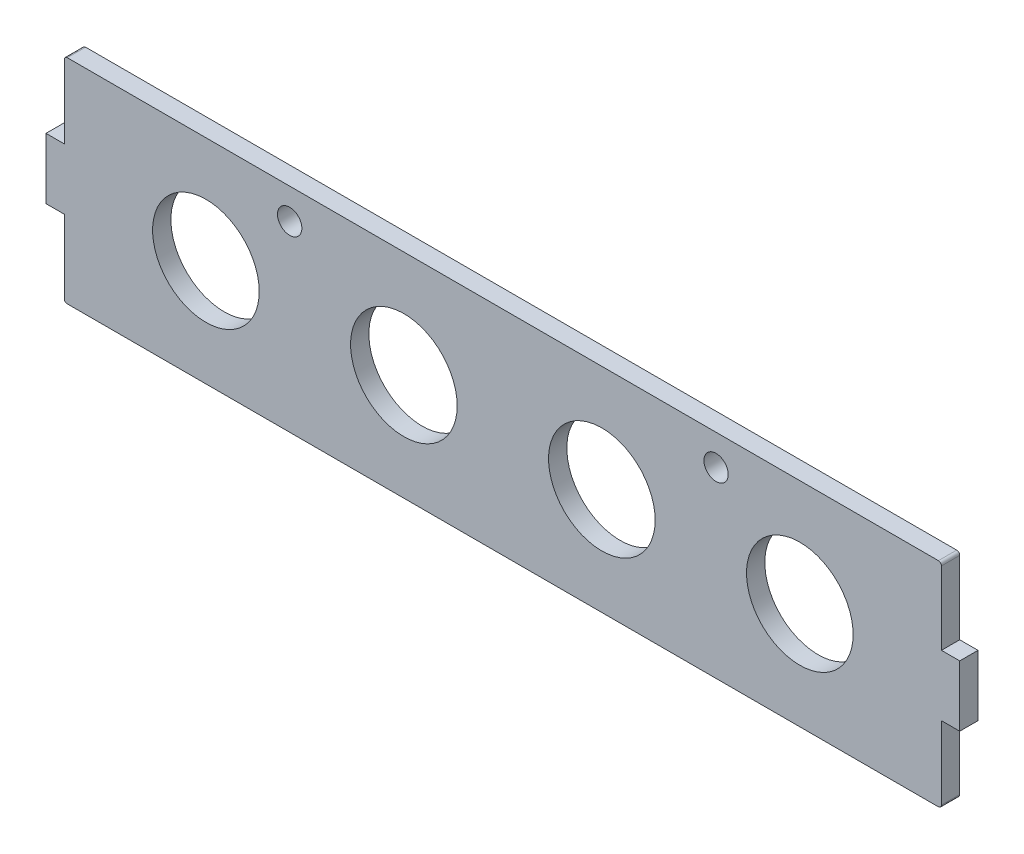
SolidWorks part; units mm, degrees
material "Beech"
ref_plane "Спереди" through (0, 0, 0) normal (0, 0, 1) x (1, 0, 0)
ref_plane "Сверху" through (0, 0, 0) normal (0, 1, 0) x (1, 0, 0)
ref_plane "Справа" through (0, 0, 0) normal (1, 0, 0) x (0, 0, -1)
sketch "Sketch1" plane through (0, 0, 0) normal (0, 0, 1) x (1, 0, 0)
  line L1 (0, 0) -> (300, 0)
  line L2 (0, 0) -> (0, 70)
  line L3 (0, 70) -> (300, 70)
  line L4 (300, 0) -> (300, 70)
  dimension "D1" = 70
  dimension "D2" = 300
extrude "front" add sketch "Sketch1" against normal blind 6
sketch "Sketch2" plane through (0, 0, 0) normal (0, 0, 1) x (1, 0, 0)
  line L0 (6, 70) -> (6, 45)
  line L1 (300, 70) -> (0, 70) construction
  line L2 (6, 45) -> (0, 45)
  line L3 (0, 70) -> (0, 0) construction
  line L4 (0, 25) -> (6, 25)
  line L5 (6, 25) -> (6, 0)
  line L6 (0, 0) -> (300, 0) construction
  line L7 (0, 45) -> (0, 25)
  line L8 (6, 70) -> (0, 70)
  line L9 (0, 70) -> (0, 45)
  line L10 (80, 60) -> (220, 60) construction
  line L11 (0, 25) -> (0, 0)
  line L12 (0, 0) -> (6, 0)
  line L13 (294, 70) -> (294, 45)
  line L14 (294, 45) -> (300, 45)
  line L15 (300, 0) -> (300, 70) construction
  line L16 (300, 45) -> (300, 70)
  line L17 (300, 70) -> (294, 70)
  line L18 (300, 25) -> (294, 25)
  line L19 (294, 25) -> (294, 0)
  line L20 (294, 0) -> (300, 0)
  line L21 (300, 0) -> (300, 25)
  circle A0 centre (80, 60) radius 4
  circle A1 centre (220, 60) radius 4
  point P32 (150, 60)
  point P33 (150, 70)
  line M1 (0, 70) -> (0, 0)
  line M2 (0, 0) -> (300, 0)
  line M4 (300, 70) -> (0, 70)
  dimension "D3" = 8
  dimension "D4" = 10
  dimension "D1" = 6
  dimension "D2" = 20
  dimension "D5" = 140
extrude "mount" cut sketch "Sketch2" against normal through all contours L2 L0 M4 M1 | L5 L4 M1 M2 | L16 L17 L13 L14 | L21 L18 L19 L20 | A0 | A1
fillet "fillet" radius 1 4 edges at (294, 0, -3) (294, 70, -3) (6, 0, -3) (6, 70, -3)
sketch "Sketch3" plane through (0, 0, 0) normal (0, 0, 1) x (1, 0, 0)
  line L0 (52.5, 35) -> (117.5, 35) construction
  line L1 (117.5, 35) -> (182.5, 35) construction
  line L2 (182.5, 35) -> (247.5, 35) construction
  line L3 (7, 0) -> (293, 0) construction
  circle A0 centre (52.5, 35) radius 17.5
  circle A1 centre (117.5, 35) radius 17.5
  circle A2 centre (182.5, 35) radius 17.5
  circle A3 centre (247.5, 35) radius 17.5
  point P8 (150, 35)
  point P9 (150, 0)
  dimension "D2" = 35
  dimension "D3" = 35
  dimension "D1" = 65
extrude "lite" cut sketch "Sketch3" against normal through all
